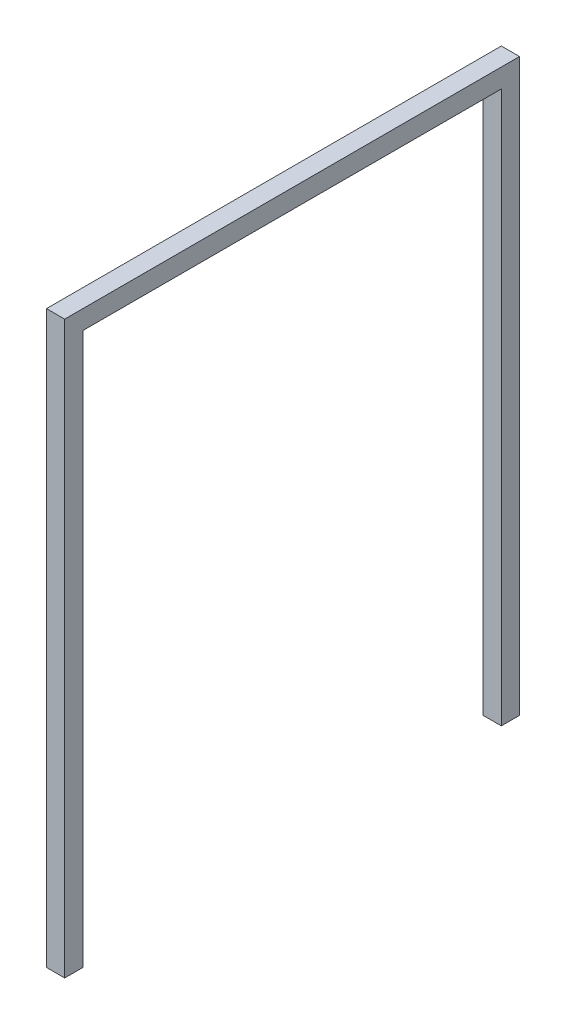
SolidWorks part; units mm, degrees
material "Stainless Steel (ferritic)"
ref_plane "Front Plane" through (0, 0, 0) normal (0, 0, 1) x (1, 0, 0)
ref_plane "Top Plane" through (0, 0, 0) normal (0, 1, 0) x (1, 0, 0)
ref_plane "Right Plane" through (0, 0, 0) normal (1, 0, 0) x (0, 0, -1)
sketch "Sketch2" plane through (0, 0, 0) normal (0, 1, 0) x (1, 0, 0)
  line L1 (0, 0) -> (24.2957, 0)
  line L2 (0, 0) -> (0, 24.2957)
  line L3 (0, 24.2957) -> (24.2957, 24.2957)
  line L4 (24.2957, 0) -> (24.2957, 24.2957)
  line L6 (0, 583.0957) -> (24.2957, 583.0957)
  line L7 (0, 583.0957) -> (0, 607.3913)
  line L8 (0, 607.3913) -> (24.2957, 607.3913)
  line L9 (24.2957, 583.0957) -> (24.2957, 607.3913)
  point P9 (0, 0)
  point P10 (0, 0)
  dimension "D1" = 558.8
extrude "Boss-Extrude1" add sketch "Sketch2" along normal blind 762
sketch "Sketch3" plane through (0, 0, -583.0957) normal (0, 0, 1) x (1, 0, 0)
  line L0 (24.2957, 762) -> (24.2957, 0) construction
  line L1 (0, 762) -> (24.2957, 762)
  line L2 (0, 762) -> (0, 736.6)
  line L3 (0, 736.6) -> (24.2957, 736.6)
  line L4 (24.2957, 762) -> (24.2957, 736.6)
extrude "Boss-Extrude2" add sketch "Sketch3" along normal blind 558.8
